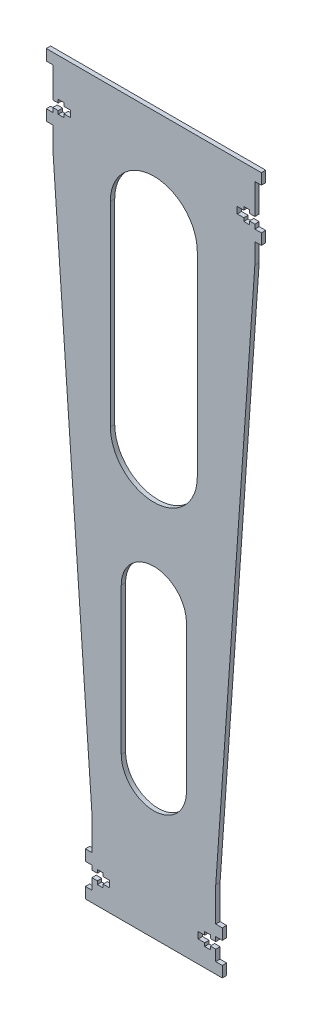
SolidWorks part; units mm, degrees
ref_plane "前视基准面" through (0, 0, 0) normal (0, 0, 1) x (1, 0, 0)
ref_plane "上视基准面" through (0, 0, 0) normal (0, 1, 0) x (1, 0, 0)
ref_plane "右视基准面" through (0, 0, 0) normal (1, 0, 0) x (0, 0, -1)
sketch "草图1" plane through (0, 0, 0) normal (0, 0, 1) x (1, 0, 0)
  line L156 (26.2338, -52.5745) -> (29.2338, -52.5745)
  line L158 (29.2338, -62.5745) -> (26.2338, -62.5745)
  line L223 (26.2338, -52.5745) -> (26.2338, -56.0745) construction
  line L224 (26.2338, -56.0745) -> (24.874, -56.0745) construction
  line L225 (26.2338, -54.5745) -> (26.2338, -57.5745) construction
  line L227 (26.2338, -54.5745) -> (26.2338, -52.5745)
  line L228 (23.7338, -54.5745) -> (23.7338, -53.0745)
  line L229 (23.7338, -57.5745) -> (23.7338, -59.0745)
  line L230 (26.2338, -57.5745) -> (23.7338, -57.5745)
  line L231 (23.7338, -53.0745) -> (21.1338, -53.0745)
  line L232 (21.1338, -53.0745) -> (21.1338, -54.5745)
  line L233 (21.1338, -54.5745) -> (18.1338, -54.5745)
  line L234 (18.1338, -57.5745) -> (18.1338, -54.5745)
  line L235 (21.1338, -57.5745) -> (18.1338, -57.5745)
  line L236 (21.1338, -59.0745) -> (21.1338, -57.5745)
  line L237 (23.7338, -54.5745) -> (26.2338, -54.5745)
  line L238 (23.7338, -59.0745) -> (21.1338, -59.0745)
  line L242 (29.2338, -62.5745) -> (29.2338, -67.5745)
  line L251 (29.2338, -52.5745) -> (29.2338, -47.5745)
  line L252 (29.2338, -47.5745) -> (26.2338, -47.5745)
  line L258 (26.2338, -62.5745) -> (26.2338, -57.5745)
  line L260 (29.2338, -67.5745) -> (26.2338, -67.5745)
  line L267 (-30.7662, -54.5745) -> (-30.7662, -57.5745) construction
  line L268 (-30.7662, -56.0745) -> (-29.4063, -56.0745) construction
  line L269 (-30.7662, -52.5745) -> (-30.7662, -56.0745) construction
  line L270 (-30.7662, -62.5745) -> (-30.7662, -57.5745)
  line L272 (-33.7662, -47.5745) -> (-30.7662, -47.5745)
  line L273 (-33.7662, -52.5745) -> (-33.7662, -47.5745)
  line L274 (-28.2662, -59.0745) -> (-25.6662, -59.0745)
  line L275 (-28.2662, -54.5745) -> (-30.7662, -54.5745)
  line L276 (-25.6662, -59.0745) -> (-25.6662, -57.5745)
  line L277 (-25.6662, -57.5745) -> (-22.6662, -57.5745)
  line L278 (-22.6662, -57.5745) -> (-22.6662, -54.5745)
  line L279 (-25.6662, -54.5745) -> (-22.6662, -54.5745)
  line L280 (-25.6662, -53.0745) -> (-25.6662, -54.5745)
  line L281 (-28.2662, -53.0745) -> (-25.6662, -53.0745)
  line L282 (-30.7662, -57.5745) -> (-28.2662, -57.5745)
  line L283 (-28.2662, -57.5745) -> (-28.2662, -59.0745)
  line L284 (-28.2662, -54.5745) -> (-28.2662, -53.0745)
  line L285 (-30.7662, -54.5745) -> (-30.7662, -52.5745)
  line L286 (-33.7662, -62.5745) -> (-30.7662, -62.5745)
  line L287 (-30.7662, -52.5745) -> (-33.7662, -52.5745)
  line L288 (-33.7662, -62.5745) -> (-33.7662, -67.5745)
  line L289 (-33.7662, -67.5745) -> (-30.7662, -67.5745)
  line L292 (26.2338, -67.5745) -> (-30.7662, -67.5745)
  line L300 (-48.7662, 224.1255) -> (-48.7662, 233.4755)
  line L310 (44.2338, 233.4755) -> (44.2338, 224.1255)
  line L311 (-30.7662, -31.9383) -> (26.2338, -31.9383) construction
  line L312 (-48.7662, 224.1255) -> (-30.7662, -31.9383)
  line L322 (-30.7662, -31.9383) -> (-30.7662, -47.5745)
  line L323 (26.2338, -31.9383) -> (26.2338, -47.5745)
  line L325 (44.2338, 224.1255) -> (26.2338, -31.9383)
  line L326 (-48.7662, 224.1255) -> (44.2338, 224.1255) construction
  line L327 (-2.2662, -31.9383) -> (-2.2662, 96.0617) construction
  line L328 (-48.7662, 233.4755) -> (-51.7662, 233.4755)
  line L329 (-51.7662, 233.4755) -> (-51.7662, 238.4755)
  line L330 (-51.7662, 238.4755) -> (-48.7662, 238.4755)
  line L331 (-46.2662, 240.4755) -> (-46.2662, 238.9755)
  line L332 (-46.2662, 243.4755) -> (-46.2662, 244.9755)
  line L333 (-48.7662, 243.4755) -> (-46.2662, 243.4755)
  line L334 (-46.2662, 238.9755) -> (-43.6662, 238.9755)
  line L335 (-43.6662, 238.9755) -> (-43.6662, 240.4755)
  line L336 (-43.6662, 240.4755) -> (-40.6662, 240.4755)
  line L337 (-40.6662, 243.4755) -> (-40.6662, 240.4755)
  line L338 (-43.6662, 243.4755) -> (-40.6662, 243.4755)
  line L339 (-43.6662, 244.9755) -> (-43.6662, 243.4755)
  line L340 (-46.2662, 244.9755) -> (-43.6662, 244.9755)
  line L341 (-46.2662, 240.4755) -> (-48.7662, 240.4755)
  line L342 (-48.7662, 238.4755) -> (-48.7662, 240.4755)
  line L343 (-48.7662, 243.4755) -> (-48.7662, 248.4755)
  line L344 (-48.7662, 257.4755) -> (-51.7662, 257.4755)
  line L345 (-51.7662, 257.4755) -> (-51.7662, 262.4755)
  line L346 (-51.7662, 262.4755) -> (-48.7662, 262.4755)
  line L347 (47.2338, 262.4755) -> (44.2338, 262.4755)
  line L348 (47.2338, 257.4755) -> (47.2338, 262.4755)
  line L349 (44.2338, 257.4755) -> (47.2338, 257.4755)
  line L350 (44.2338, 243.4755) -> (44.2338, 248.4755)
  line L351 (44.2338, 238.4755) -> (44.2338, 240.4755)
  line L352 (41.7338, 240.4755) -> (44.2338, 240.4755)
  line L353 (41.7338, 244.9755) -> (39.1338, 244.9755)
  line L354 (39.1338, 244.9755) -> (39.1338, 243.4755)
  line L355 (39.1338, 243.4755) -> (36.1338, 243.4755)
  line L356 (36.1338, 243.4755) -> (36.1338, 240.4755)
  line L357 (39.1338, 240.4755) -> (36.1338, 240.4755)
  line L358 (39.1338, 238.9755) -> (39.1338, 240.4755)
  line L359 (41.7338, 238.9755) -> (39.1338, 238.9755)
  line L360 (44.2338, 243.4755) -> (41.7338, 243.4755)
  line L361 (41.7338, 243.4755) -> (41.7338, 244.9755)
  line L362 (41.7338, 240.4755) -> (41.7338, 238.9755)
  line L363 (47.2338, 238.4755) -> (44.2338, 238.4755)
  line L364 (44.2338, 233.4755) -> (47.2338, 233.4755)
  line L365 (47.2338, 233.4755) -> (47.2338, 238.4755)
  line L366 (-48.7662, 257.4755) -> (-48.7662, 248.4755)
  line L367 (-2.2662, -1.6722) -> (-2.2662, 65.7956) construction
  line L368 (-17.2662, -1.6722) -> (-17.2662, 65.7956)
  line L369 (12.7338, -1.6722) -> (12.7338, 65.7956)
  line L370 (44.2338, 257.4755) -> (44.2338, 248.4755)
  line L371 (-2.2662, 216.3278) -> (-2.2662, 126.3278) construction
  line L372 (-22.2662, 216.3278) -> (-22.2662, 126.3278)
  line L373 (17.7338, 216.3278) -> (17.7338, 126.3278)
  line L374 (-48.7662, 262.4755) -> (44.2338, 262.4755)
  arc A0 (-17.2662, -1.6722) -> (12.7338, -1.6722) centre (-2.2662, -1.6722) ccw
  arc A1 (12.7338, 65.7956) -> (-17.2662, 65.7956) centre (-2.2662, 65.7956) ccw
  arc A2 (-22.2662, 216.3278) -> (17.7338, 216.3278) centre (-2.2662, 216.3278) cw
  arc A3 (17.7338, 126.3278) -> (-22.2662, 126.3278) centre (-2.2662, 126.3278) cw
  point P35 (-22.1662, -55.5745)
  point P39 (-2.2662, 32.0617)
  point P56 (17.6338, -55.5745)
  point P63 (-2.2662, 171.3278)
  point P68 (0, 0)
extrude "凸台-拉伸1" add sketch "草图1" along normal blind 2
sketch "草图3" plane through (26.2338, 0, 0) normal (1, 0, 0) x (0, 0, -1)
  line L0 (0, -57.5745) -> (-2, -54.5745)
  circle A0 centre (-1, -56.0745) radius 1.5
sketch "草图5" plane through (-30.7662, 0, 0) normal (-1, 0, 0) x (0, 0, 1)
  line L0 (2, -57.5745) -> (0, -54.5745)
  circle A0 centre (1, -56.0745) radius 1.5
